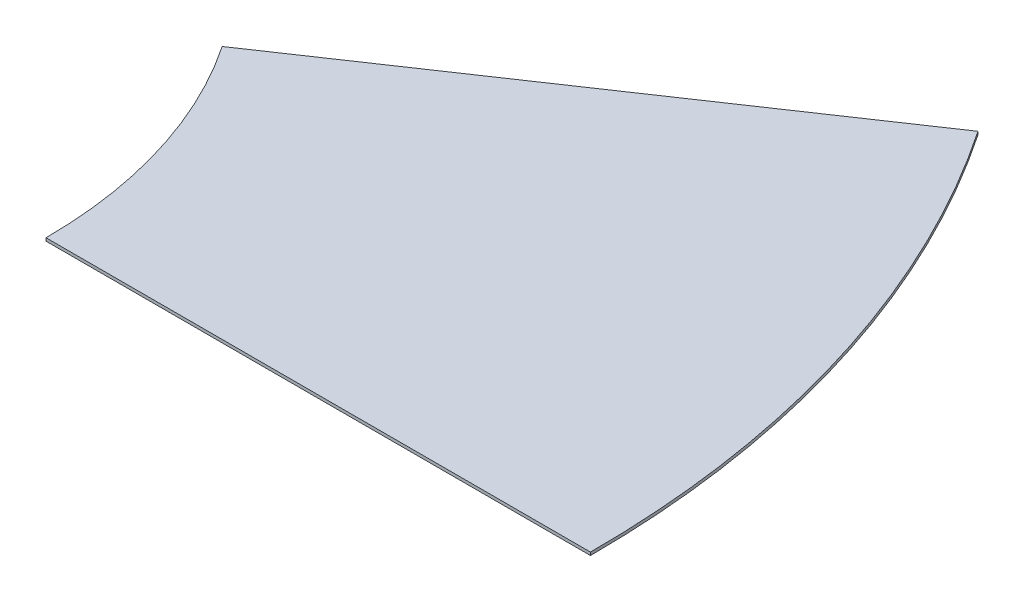
SolidWorks part; units mm, degrees
ref_plane "Front" through (0, 0, 0) normal (0, 0, 1) x (1, 0, 0)
ref_plane "Top" through (0, 0, 0) normal (0, 1, 0) x (1, 0, 0)
ref_plane "Right" through (0, 0, 0) normal (1, 0, 0) x (0, 0, -1)
sketch "草图1" plane through (0, 0, 0) normal (0, 1, 0) x (1, 0, 0)
  line L0 (0, 0) -> (110, 0) construction
  line L1 (91.1941, 61.5112) -> (0, 0) construction
  line L2 (91.1941, 61.5112) -> (41.4519, 27.9596)
  line L3 (110, 0) -> (50, 0)
  arc A0 (110, 0) -> (91.1941, 61.5112) centre (0, 0) ccw
  arc A1 (50, 0) -> (41.4519, 27.9596) centre (0, 0) ccw
  dimension "D2" = 50
  dimension "D3" = 110
  dimension "D1" = 34
extrude "凸台-拉伸1" add sketch "草图1" along normal blind 0.33 contours L3 A1 L2 A0
